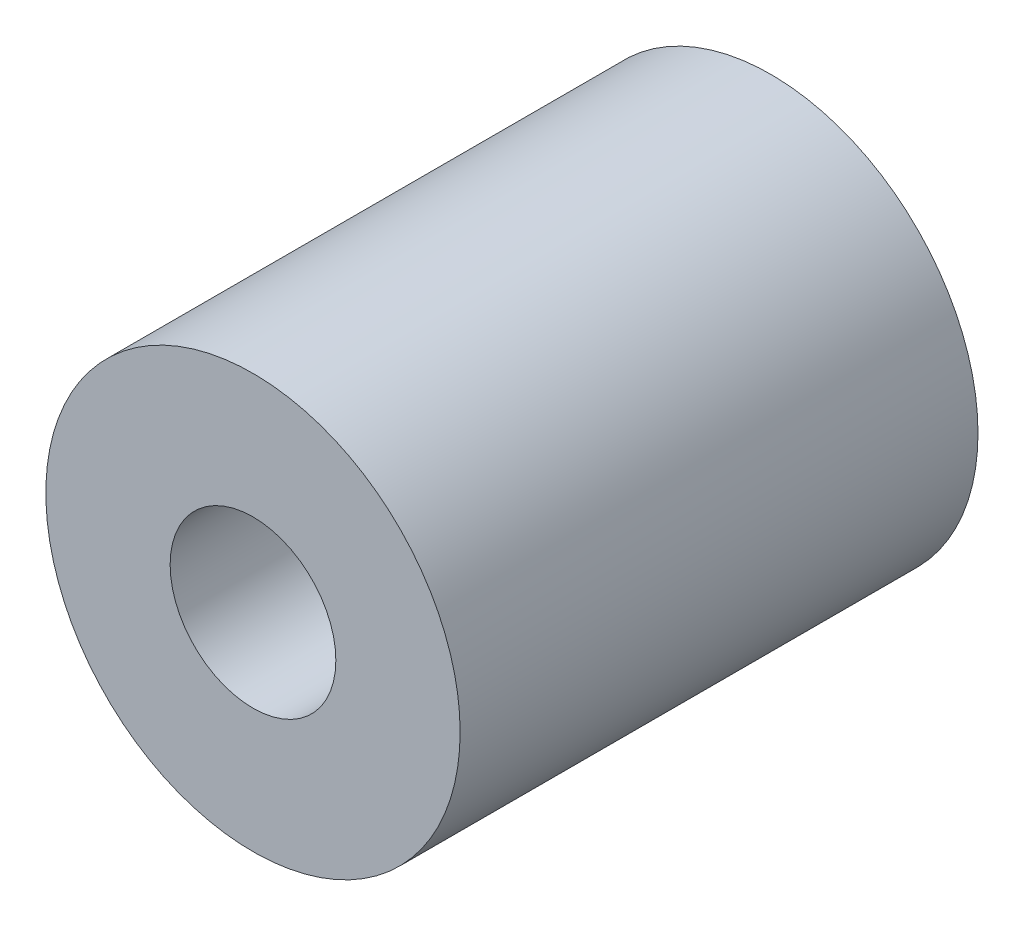
SolidWorks part; units mm, degrees
ref_plane "前视基准面" through (0, 0, 0) normal (0, 0, 1) x (1, 0, 0)
ref_plane "上视基准面" through (0, 0, 0) normal (0, 1, 0) x (1, 0, 0)
ref_plane "右视基准面" through (0, 0, 0) normal (1, 0, 0) x (0, 0, -1)
sketch "草图1" plane through (0, 0, 0) normal (0, 0, 1) x (1, 0, 0)
  circle A0 centre (0, 0) radius 4
  circle A1 centre (0, 0) radius 10
  dimension "D1" = 20
  dimension "D2" = 8
extrude "凸台-拉伸1" add sketch "草图1" along normal blind 25
sketch "草图2" plane through (0, 0, 0) normal (0, 0, -1) x (-1, 0, 0)
  circle A0 centre (0, 0) radius 5
  dimension "D1" = 10
extrude "切除-拉伸1" cut sketch "草图2" against normal blind 10
